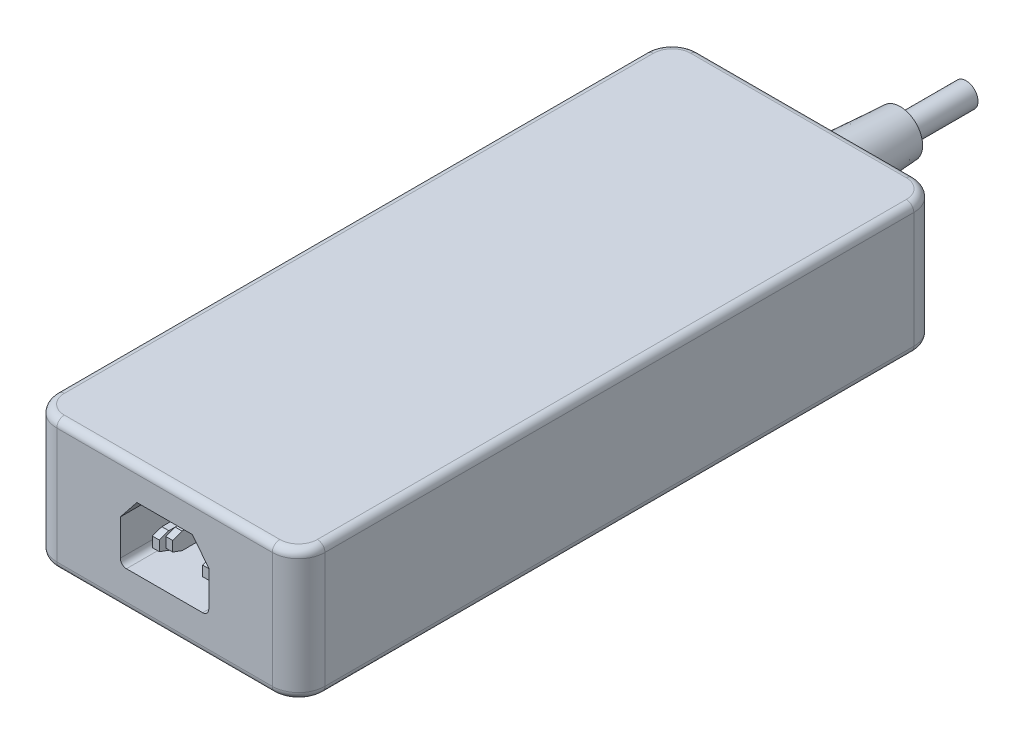
SolidWorks part; units mm, degrees
ref_plane "Front Plane" through (0, 0, 0) normal (0, 0, 1) x (1, 0, 0)
ref_plane "Top Plane" through (0, 0, 0) normal (0, 1, 0) x (1, 0, 0)
ref_plane "Right Plane" through (0, 0, 0) normal (1, 0, 0) x (0, 0, -1)
sketch "Sketch1" plane through (0, 0, 0) normal (0, 0, 1) x (1, 0, 0)
  line L0 (36.195, 17.6784) -> (-36.195, -17.6784) construction
  line L1 (-36.195, 17.6784) -> (36.195, 17.6784)
  line L2 (-36.195, 17.6784) -> (-36.195, -17.6784)
  line L3 (-36.195, -17.6784) -> (36.195, -17.6784)
  line L4 (36.195, 17.6784) -> (36.195, -17.6784)
  dimension "D1" = 35.3568
  dimension "D2" = 72.39
extrude "Boss-Extrude1" add sketch "Sketch1" along normal mid plane 173.228
fillet "Fillet1" radius 7.112 4 edges at (36.195, 0, -86.614) (-36.195, 0, -86.614) (36.195, 0, 86.614) (-36.195, 0, 86.614)
fillet "Fillet2" radius 2.032 16 edges at (-34.1119, -17.6784, -84.5309) (-36.195, -17.6784, 0) (-34.1119, -17.6784, 84.5309) (0, -17.6784, 86.614) (34.1119, -17.6784, 84.5309) (36.195, -17.6784, 0) (34.1119, -17.6784, -84.5309) (0, -17.6784, -86.614) (34.1119, 17.6784, 84.5309) (0, 17.6784, 86.614) (-34.1119, 17.6784, 84.5309) (-36.195, 17.6784, 0) (-34.1119, 17.6784, -84.5309) (0, 17.6784, -86.614) (34.1119, 17.6784, -84.5309) (36.195, 17.6784, 0)
sketch "Sketch2" plane through (0, 0, 86.614) normal (0, 0, 1) x (1, 0, 0)
  line L0 (0, 0) -> (0, 15.6464) construction
  line L1 (29.083, 15.6464) -> (-29.083, 15.6464) construction
  line L2 (0, 0) -> (-29.083, 0) construction
  line L3 (-29.083, 15.6464) -> (-29.083, -15.6464) construction
  line L4 (7.474, 9.0551) -> (-7.474, 9.0551)
  line L5 (-7.474, 9.0551) -> (-11.938, 3.4544)
  line L6 (-11.938, 3.4544) -> (-11.938, -7.8359)
  line L7 (-11.938, -7.8359) -> (11.938, -7.8359)
  line L8 (11.938, 3.4544) -> (11.938, -7.8359)
  line L9 (7.474, 9.0551) -> (11.938, 3.4544)
  line L10 (29.083, -17.6784) -> (-29.083, -17.6784) construction
  point P5 (0, -7.8359)
  point P16 (0, 9.0551)
  dimension "D1" = 16.891
  dimension "D2" = 23.876
  dimension "D3" = 9.8425
  dimension "D4" = 14.9479
  dimension "D5" = 11.2903
extrude "Cut-Extrude1" cut sketch "Sketch2" against normal blind 17.0561
fillet "Fillet3" radius 1.651 2 edges at (11.938, -7.8359, 78.0859) (-11.938, -7.8359, 78.0859)
sketch "Sketch3" plane through (0, 0, 69.5579) normal (0, 0, 1) x (1, 0, 0)
  line L0 (0, 0) -> (0, -7.8359) construction
  line L1 (-7.7216, -0.2159) -> (-5.842, -0.2159)
  line L2 (-7.7216, -0.2159) -> (-7.7216, -4.7879)
  line L3 (-7.7216, -4.7879) -> (-5.842, -4.7879)
  line L4 (-5.842, -0.2159) -> (-5.842, -4.7879)
  line L5 (-0.9398, 4.6736) -> (0.9398, 4.6736)
  line L6 (-0.9398, 4.6736) -> (-0.9398, 0.1016)
  line L7 (-0.9398, 0.1016) -> (0.9398, 0.1016)
  line L8 (0.9398, 4.6736) -> (0.9398, 0.1016)
  line L9 (-10.287, -7.8359) -> (10.287, -7.8359) construction
  line L10 (5.842, -0.2159) -> (5.842, -4.7879)
  line L11 (7.7216, -4.7879) -> (5.842, -4.7879)
  line L12 (7.7216, -0.2159) -> (7.7216, -4.7879)
  line L13 (7.7216, -0.2159) -> (5.842, -0.2159)
  line L14 (-10.287, -7.8359) -> (10.287, -7.8359) construction
  line L15 (0, 0) -> (0, 0.1016) construction
  dimension "D1" = 1.8796
  dimension "D2" = 4.572
  dimension "D3" = 3.048
  dimension "D4" = 11.684
  dimension "D5" = 7.9375
extrude "Boss-Extrude2" add sketch "Sketch3" along normal offset from surface (15.7861 mm away) 1.27 up to face at (0, -0.4633, 86.614)
sketch "Sketch4" plane through (0, 0, 85.344) normal (0, 0, 1) x (1, 0, 0)
  line L0 (7.7216, -4.7879) -> (7.7216, -0.2159) construction
  line L1 (-7.7216, -4.7879) -> (7.7216, -4.7879)
  line L2 (-7.7216, -4.7879) -> (-7.7216, -0.2159)
  line L3 (-7.7216, -0.2159) -> (7.7216, -0.2159)
  line L4 (7.7216, -4.7879) -> (7.7216, -0.2159)
extrude "Cut-Extrude2" cut sketch "Sketch4" against normal blind 3.175
chamfer "Chamfer1" distance 2.54 angle 20 6 edges at (0, 4.6736, 85.344) (0, 0.1016, 85.344) (-6.7818, -4.7879, 82.169) (6.7818, -4.7879, 82.169) (6.7818, -0.2159, 82.169) (-6.7818, -0.2159, 82.169)
sketch "Sketch5" plane through (0, 0, -86.614) normal (0, 0, -1) x (-1, 0, 0)
  circle A0 centre (0, 0) radius 7.62
  dimension "D1" = 15.24
extrude "Boss-Extrude3" add sketch "Sketch5" along normal blind 25.4 draft 3.5
sketch "Sketch7" plane through (0, 0, -112.014) normal (0, 0, -1) x (-1, 0, 0)
  circle A0 centre (0, 0) radius 3.2385
  dimension "D1" = 6.477
extrude "Boss-Extrude4" add sketch "Sketch7" along normal blind 32.766
sketch "Sketch8" plane through (0, 0, -144.78) normal (0, 0, -1) x (-1, 0, 0)
  circle A0 centre (0, 0) radius 10.8966
  dimension "D1" = 21.7932
extrude "Boss-Extrude5" add sketch "Sketch8" along normal blind 34.417
fillet "Fillet4" radius 0.635 2 edges at (-10.8966, 0, -144.78) (-10.8966, 0, -179.197)
sketch "Sketch9" plane through (0, 0, -179.197) normal (0, 0, -1) x (-1, 0, 0)
  circle A0 centre (0, 0) radius 3.2385 construction
  circle A1 centre (0, 0) radius 3.2385
extrude "Boss-Extrude6" add sketch "Sketch9" along normal blind 34.417
sketch "Sketch10" plane through (0, 0, -213.614) normal (0, 0, -1) x (-1, 0, 0)
  circle A0 centre (0, 0) radius 27.9004
extrude "Cut-Extrude3" cut sketch "Sketch10" against normal blind 83.82
